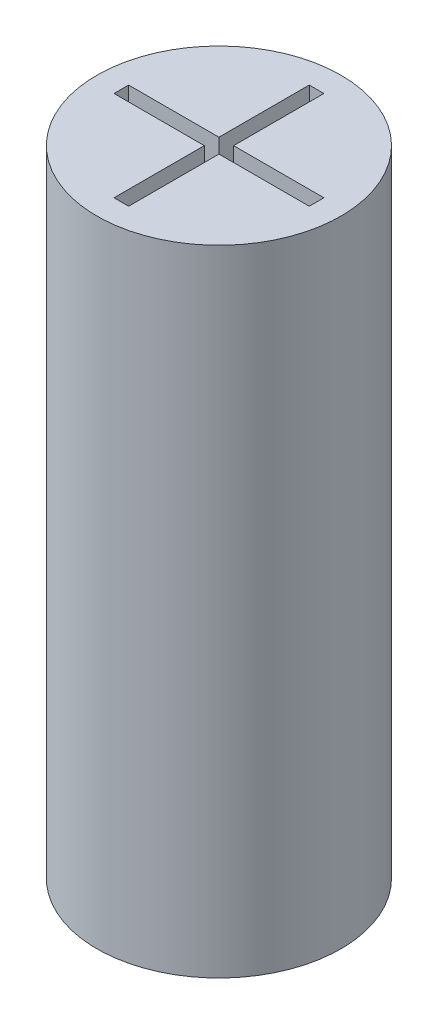
SolidWorks part; units mm, degrees
ref_plane "Front Plane" through (0, 0, 0) normal (0, 0, 1) x (1, 0, 0)
ref_plane "Top Plane" through (0, 0, 0) normal (0, 1, 0) x (1, 0, 0)
ref_plane "Right Plane" through (0, 0, 0) normal (1, 0, 0) x (0, 0, -1)
sketch "Sketch2" plane through (0, 0, 0) normal (0, 1, 0) x (1, 0, 0)
  circle A0 centre (0, 0) radius 2.5
extrude "Boss-Extrude1" add sketch "Sketch2" along normal blind 13
sketch "Sketch3" plane through (0, 13, 0) normal (0, 1, 0) x (1, 0, 0)
  line L1 (0.15, 2) -> (-0.15, 2)
  line L2 (0.15, 2) -> (0.15, -2)
  line L3 (0.15, -2) -> (-0.15, -2)
  line L4 (-0.15, 2) -> (-0.15, -2)
  line L5 (0.15, 2) -> (-0.15, -2) construction
  line L6 (0.15, -2) -> (-0.15, 2) construction
  line L7 (-2, 0.15) -> (2, 0.15)
  line L8 (-2, 0.15) -> (-2, -0.15)
  line L9 (-2, -0.15) -> (2, -0.15)
  line L10 (2, 0.15) -> (2, -0.15)
  line L11 (-2, 0.15) -> (2, -0.15) construction
  line L12 (-2, -0.15) -> (2, 0.15) construction
  point P0 (0, 0)
  point P6 (0, 0)
  dimension "D1" = 0.3
  dimension "D2" = 4
  dimension "D3" = 4
  dimension "D4" = 0.3
extrude "Cut-Extrude1" cut sketch "Sketch3" against normal blind 1 contours L10 L7 L2 L9 | L4 L9 L2 L7 | L8 L9 L4 L7 | L4 L7 L2 L1 | L9 L4 L3 L2
